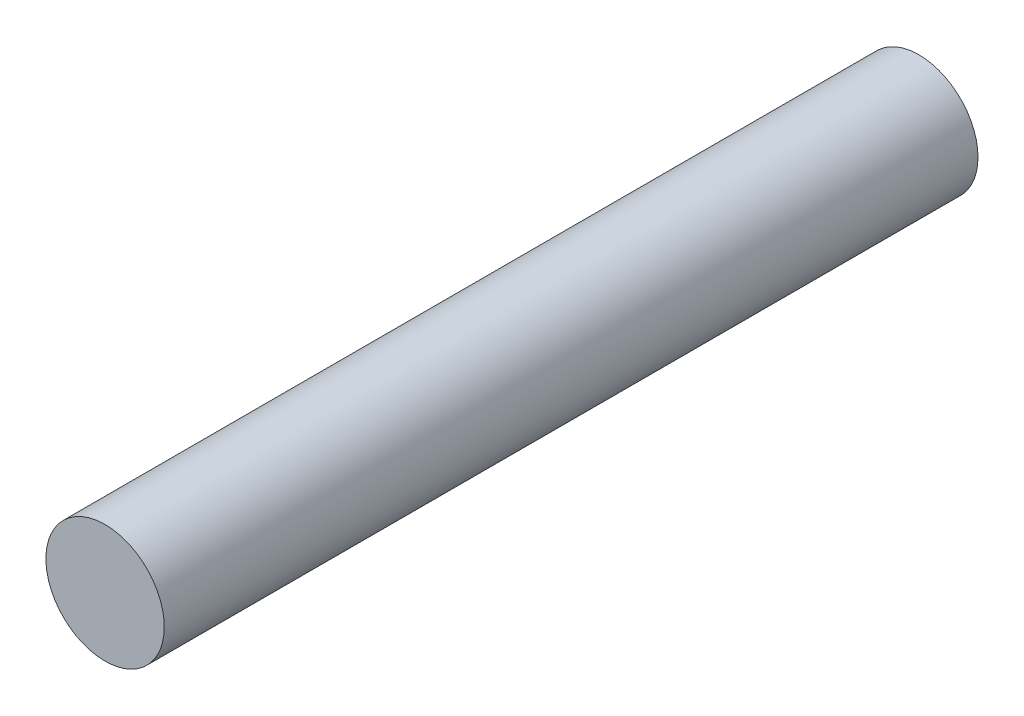
SolidWorks part; units mm, degrees
ref_plane "前视基准面" through (0, 0, 0) normal (0, 0, 1) x (1, 0, 0)
ref_plane "上视基准面" through (0, 0, 0) normal (0, 1, 0) x (1, 0, 0)
ref_plane "右视基准面" through (0, 0, 0) normal (1, 0, 0) x (0, 0, -1)
sketch "草图1" plane through (0, 0, 0) normal (0, 0, 1) x (1, 0, 0)
  circle A0 centre (0, 0) radius 4
  dimension "D1" = 8
extrude "凸台-拉伸1" add sketch "草图1" along normal blind 55
